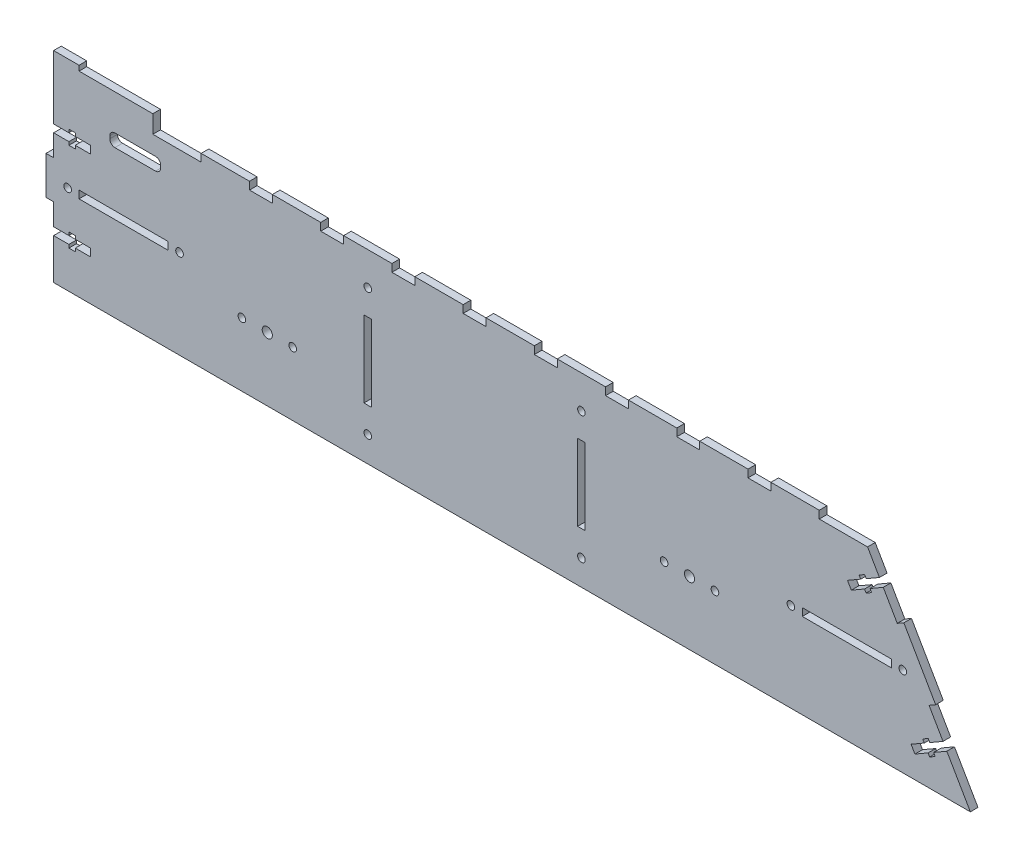
SolidWorks part; units mm, degrees
ref_plane "Спереди" through (0, 0, 0) normal (0, 0, 1) x (1, 0, 0)
ref_plane "Сверху" through (0, 0, 0) normal (0, 1, 0) x (1, 0, 0)
ref_plane "Справа" through (0, 0, 0) normal (1, 0, 0) x (0, 0, -1)
sketch "Эскиз1" plane through (0, 0, 0) normal (0, 0, 1) x (1, 0, 0)
  line L0 (320, 70) -> (360.4145, 0)
  line L2 (0, 0) -> (0, 70)
  line L3 (0, 70) -> (320, 70)
  line L5 (0, 0) -> (360.4145, 0)
  circle A0 centre (84, 25) radius 2
  circle A1 centre (250, 25) radius 2
  circle A2 centre (84, 25) radius 10 construction
  circle A3 centre (94, 25) radius 1.5
  circle A4 centre (74, 25) radius 1.5
  circle A5 centre (240, 25) radius 1.5
  circle A6 centre (260, 25) radius 1.5
  circle A7 centre (250, 25) radius 10 construction
  dimension "D4" = 4
  dimension "D8" = 20
  dimension "D9" = 3
  dimension "D10" = 80.829
  dimension "D1" = 320
  dimension "D2" = 70
  dimension "D3" = 60
  dimension "D5" = 25
  dimension "D6" = 166
  dimension "D7" = 84
extrude "Бобышка-Вытянуть1" add sketch "Эскиз1" along normal blind 3
sketch "Эскиз2" plane through (0, 70, 0) normal (0, 1, 0) x (1, 0, 0)
  line L0 (320, -3) -> (0, -3) construction
  line L1 (301, -3) -> (282, -3)
  line L2 (301, -3) -> (301, 0)
  line L3 (301, 0) -> (282, 0)
  line L4 (282, -3) -> (282, 0)
  line L5 (320, 0) -> (0, 0) construction
  dimension "D1" = 19
  dimension "D2" = 19
extrude "Бобышка-Вытянуть2" add sketch "Эскиз2" along normal blind 3
pattern_linear "Линейный массив1" count 9 spacing 28 along (-1, 0, 0) of "Бобышка-Вытянуть2"
sketch "Эскиз3" plane through (0, 0, 3) normal (0, 0, 1) x (1, 0, 0)
  line L0 (198, 73) -> (217, 73) construction
  line L1 (206, 50) -> (209, 50)
  line L2 (206, 50) -> (206, 20)
  line L3 (206, 20) -> (209, 20)
  line L4 (209, 50) -> (209, 20)
  line L5 (206, 50) -> (209, 20) construction
  line L6 (206, 20) -> (209, 50) construction
  line L7 (0, 70) -> (0, 0) construction
  line L8 (114, 73) -> (133, 73) construction
  line L9 (122, 50) -> (125, 50)
  line L10 (122, 50) -> (122, 20)
  line L11 (122, 20) -> (125, 20)
  line L12 (125, 50) -> (125, 20)
  line L13 (122, 50) -> (125, 20) construction
  line L14 (122, 20) -> (125, 50) construction
  point P0 (207.5, 35)
  point P9 (207.5, 73)
  point P10 (123.5, 73)
  point P13 (0, 35)
  point P14 (123.5, 35)
  point P19 (123.5, 20)
  point P21 (207.5, 20)
  dimension "D3" = 123.5
  dimension "D1" = 30
  dimension "D2" = 3
  dimension "D4" = 84
extrude "Вырез-Вытянуть1" cut sketch "Эскиз3" against normal blind 3
sketch "Эскиз4" plane through (0, 0, 3) normal (0, 0, 1) x (1, 0, 0)
  line L0 (0, 70) -> (0, 0) construction
  line L1 (294.3412, 36.5) -> (329.3412, 36.5)
  line L2 (294.3412, 36.5) -> (294.3412, 33.5)
  line L3 (294.3412, 33.5) -> (329.3412, 33.5)
  line L4 (329.3412, 36.5) -> (329.3412, 33.5)
  line L5 (294.3412, 36.5) -> (329.3412, 33.5) construction
  line L6 (294.3412, 33.5) -> (329.3412, 36.5) construction
  line L7 (10, 36.5) -> (45, 36.5)
  line L8 (10, 36.5) -> (10, 33.5)
  line L9 (10, 33.5) -> (45, 33.5)
  line L10 (45, 36.5) -> (45, 33.5)
  line L11 (10, 36.5) -> (45, 33.5) construction
  line L12 (10, 33.5) -> (45, 36.5) construction
  line L14 (329.3412, 36.5) -> (339.3412, 36.5) construction
  line L15 (360.4145, 0) -> (320, 70) construction
  circle A0 centre (84, 25) radius 35 construction
  point P0 (311.8412, 35)
  point P5 (27.5, 35)
  point P15 (0, 35)
  point P18 (340.2073, 35)
  dimension "D5" = 70
  dimension "D1" = 35
  dimension "D2" = 3
  dimension "D3" = 10
  dimension "D4" = 10
  dimension "D6" = 40.4145
  dimension "D7" = 284.3412
extrude "Вырез-Вытянуть2" cut sketch "Эскиз4" against normal blind 3
sketch "Эскиз5" plane through (0, 0, 3) normal (0, 0, 1) x (1, 0, 0)
  line L0 (125, 50) -> (122, 50) construction
  line L1 (209, 50) -> (206, 50) construction
  line L2 (294.3412, 36.5) -> (294.3412, 33.5) construction
  line L3 (10, 36.5) -> (10, 33.5) construction
  circle A0 centre (5.5, 35) radius 1.5
  circle A1 centre (49.5, 35) radius 1.5
  circle A2 centre (123.5, 60) radius 1.5
  circle A3 centre (123.5, 10) radius 1.5
  circle A4 centre (207.5, 60) radius 1.5
  circle A5 centre (207.5, 10) radius 1.5
  circle A6 centre (289.8412, 35) radius 1.5
  circle A7 centre (333.8412, 35) radius 1.5
  point P20 (123.5, 50)
  point P29 (207.5, 50)
  point P34 (294.3412, 35)
  point P42 (10, 35)
  dimension "D1" = 3
  dimension "D2" = 10
  dimension "D3" = 10
  dimension "D4" = 4.5
  dimension "D5" = 4.5
  dimension "D6" = 4.5
  dimension "D7" = 4.5
extrude "Вырез-Вытянуть3" cut sketch "Эскиз5" against normal blind 3
sketch "Эскиз6" plane through (0, 0, 3) normal (0, 0, 1) x (1, 0, 0)
  line L0 (0, 54) -> (6, 54)
  line L1 (6, 54) -> (6, 55.25)
  line L2 (6, 55.25) -> (8.5, 55.25)
  line L3 (8.5, 55.25) -> (8.5, 54)
  line L4 (8.5, 54) -> (14.5, 54)
  line L5 (14.5, 54) -> (14.5, 51)
  line L6 (14.5, 51) -> (8.5, 51)
  line L7 (8.5, 51) -> (8.5, 49.75)
  line L8 (8.5, 49.75) -> (6, 49.75)
  line L9 (6, 49.75) -> (6, 51)
  line L10 (6, 51) -> (0, 51)
  line L13 (0, 19) -> (6, 19)
  line L14 (6, 19) -> (6, 20.25)
  line L15 (6, 20.25) -> (8.5, 20.25)
  line L16 (8.5, 20.25) -> (8.5, 19)
  line L17 (8.5, 19) -> (14.5, 19)
  line L18 (14.5, 19) -> (14.5, 16)
  line L19 (14.5, 16) -> (8.5, 16)
  line L20 (8.5, 16) -> (8.5, 14.75)
  line L21 (8.5, 14.75) -> (6, 14.75)
  line L22 (6, 14.75) -> (6, 16)
  line L23 (6, 16) -> (0, 16)
  line L24 (0, 70) -> (0, 0) construction
  line L25 (0, 0) -> (360.4145, 0) construction
  line L26 (0, 54) -> (0, 51)
  line L27 (0, 19) -> (0, 16)
  point P12 (7.25, 49.75)
  point P28 (7.25, 14.75)
  point P31 (14.5, 52.5)
  point P32 (14.5, 17.5)
  dimension "D1" = 2.5
  dimension "D2" = 3
  dimension "D3" = 5.5
  dimension "D4" = 6
  dimension "D5" = 6
  dimension "D6" = 2.5
  dimension "D7" = 3
  dimension "D8" = 5.5
  dimension "D9" = 6
  dimension "D10" = 6
  dimension "D11" = 35
  dimension "D12" = 17.5
extrude "Вырез-Вытянуть4" cut sketch "Эскиз6" against normal blind 3
sketch "Эскиз7" plane through (0, 0, 3) normal (0, 0, 1) x (1, 0, 0)
  line L0 (324.6645, 61.9208) -> (319.4684, 58.9208)
  line L1 (319.4684, 58.9208) -> (318.8434, 60.0033)
  line L2 (318.8434, 60.0033) -> (316.6783, 58.7533)
  line L3 (316.6783, 58.7533) -> (317.3033, 57.6708)
  line L4 (317.3033, 57.6708) -> (312.1072, 54.6708)
  line L5 (312.1072, 54.6708) -> (313.6072, 52.0727)
  line L6 (313.6072, 52.0727) -> (318.8033, 55.0727)
  line L7 (318.8033, 55.0727) -> (319.4283, 53.9902)
  line L8 (319.4283, 53.9902) -> (321.5934, 55.2402)
  line L9 (321.5934, 55.2402) -> (320.9684, 56.3227)
  line L10 (320.9684, 56.3227) -> (326.1645, 59.3227)
  line L11 (326.1645, 59.3227) -> (324.6645, 61.9208)
  line L12 (349.6645, 18.6195) -> (344.4684, 15.6195)
  line L13 (344.4684, 15.6195) -> (343.8434, 16.7021)
  line L14 (343.8434, 16.7021) -> (341.6783, 15.4521)
  line L15 (341.6783, 15.4521) -> (342.3033, 14.3695)
  line L16 (342.3033, 14.3695) -> (337.1072, 11.3695)
  line L17 (337.1072, 11.3695) -> (338.6072, 8.7715)
  line L18 (338.6072, 8.7715) -> (343.8033, 11.7715)
  line L19 (343.8033, 11.7715) -> (344.4283, 10.6889)
  line L20 (344.4283, 10.6889) -> (346.5934, 11.9389)
  line L21 (346.5934, 11.9389) -> (345.9684, 13.0215)
  line L22 (345.9684, 13.0215) -> (351.1645, 16.0215)
  line L23 (351.1645, 16.0215) -> (349.6645, 18.6195)
  line L24 (360.4145, 0) -> (320, 70) construction
  point P24 (350.4145, 17.3205)
  dimension "D1" = 6
  dimension "D2" = 2.5
  dimension "D3" = 3
  dimension "D4" = 5.5
  dimension "D5" = 6
  dimension "D6" = 2.5
  dimension "D7" = 3
  dimension "D8" = 5.5
  dimension "D9" = 50
  dimension "D10" = 20
extrude "Вырез-Вытянуть5" cut sketch "Эскиз7" against normal blind 3
sketch "Эскиз8" plane through (0, 70, 0) normal (0, 1, 0) x (1, 0, 0)
  line L0 (58, -3) -> (0, -3) construction
  line L1 (0, 0) -> (39, 0)
  line L2 (0, 0) -> (0, -3)
  line L3 (0, -3) -> (39, -3)
  line L4 (39, 0) -> (39, -3)
  dimension "D1" = 39
extrude "Бобышка-Вытянуть3" add sketch "Эскиз8" along normal blind 9
sketch "Эскиз9" plane through (0, 79, 0) normal (0, 1, 0) x (1, 0, 0)
  line L0 (0, -3) -> (39, -3) construction
  line L1 (39, 0) -> (10, 0)
  line L2 (39, 0) -> (39, -3)
  line L3 (39, -3) -> (10, -3)
  line L4 (10, 0) -> (10, -3)
  dimension "D1" = 10
extrude "Вырез-Вытянуть6" cut sketch "Эскиз9" against normal blind 2
sketch "Эскиз11" plane through (270.3109, 156.0641, 0) normal (0.866, 0.5, 0) x (0, 0, -1)
  line L0 (-3, -158.7073) -> (-3, -111.7073) construction
  line L1 (-3, -147.7073) -> (0, -147.7073)
  line L2 (-3, -147.7073) -> (-3, -122.7073)
  line L3 (-3, -122.7073) -> (0, -122.7073)
  line L4 (0, -147.7073) -> (0, -122.7073)
  line L5 (0, -158.7073) -> (0, -111.7073) construction
  point P9 (-3, -135.2073)
  point P10 (-3, -135.2073)
  dimension "D1" = 25
extrude "Бобышка-Вытянуть5" add sketch "Эскиз11" along normal blind 3
sketch "Эскиз12" plane through (0, 0, 0) normal (-1, 0, 0) x (0, 0, 1)
  line L0 (0, 51) -> (0, 19) construction
  line L1 (0, 27.5) -> (3, 27.5)
  line L2 (0, 27.5) -> (0, 42.5)
  line L3 (0, 42.5) -> (3, 42.5)
  line L4 (3, 27.5) -> (3, 42.5)
  line L5 (3, 51) -> (3, 19) construction
  point P9 (0, 35)
  point P10 (0, 35)
  dimension "D1" = 15
extrude "Бобышка-Вытянуть6" add sketch "Эскиз12" along normal blind 3
sketch "Эскиз13" plane through (0, 0, 3) normal (0, 0, 1) x (1, 0, 0)
  line L1 (22.0756, 57.9952) -> (42.0756, 57.9952)
  line L2 (22.0756, 57.9952) -> (22.0756, 62.9952)
  line L3 (22.0756, 62.9952) -> (42.0756, 62.9952)
  line L4 (42.0756, 57.9952) -> (42.0756, 62.9952)
  point P4 (22.0756, 57.9952)
  dimension "D1" = 5
  dimension "D2" = 20
extrude "Вырез-Вытянуть7" cut sketch "Эскиз13" against normal blind 3
fillet "Скругление1" radius 2 4 edges at (22.0756, 62.9952, 1.5) (22.0756, 57.9952, 1.5) (42.0756, 57.9952, 1.5) (42.0756, 62.9952, 1.5)
